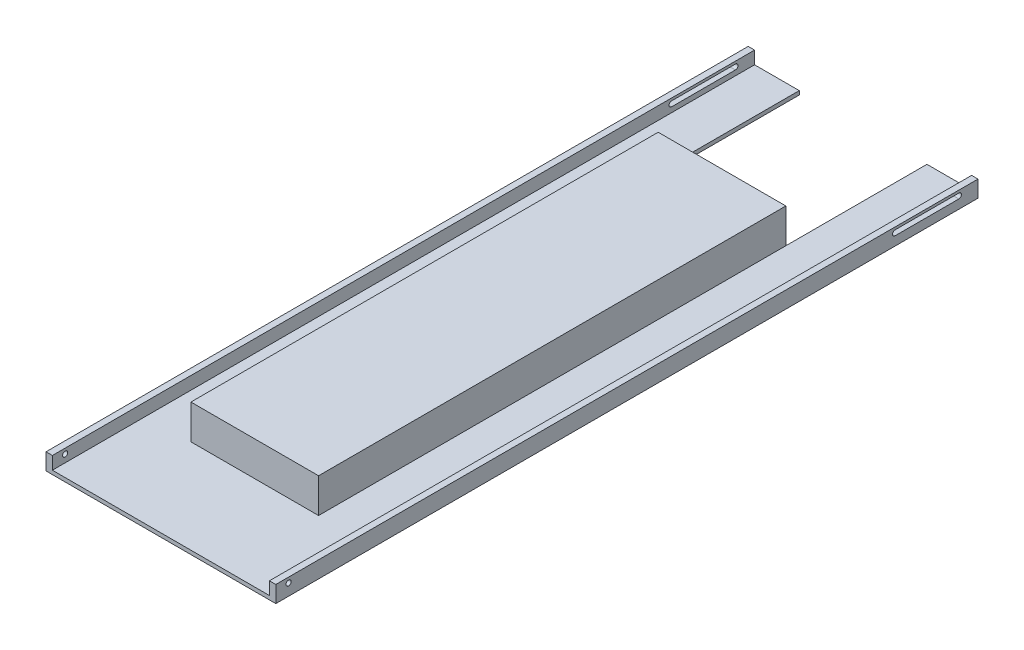
SolidWorks part; units mm, degrees
ref_plane "Front Plane" through (0, 0, 0) normal (0, 0, 1) x (1, 0, 0)
ref_plane "Top Plane" through (0, 0, 0) normal (0, 1, 0) x (1, 0, 0)
ref_plane "Right Plane" through (0, 0, 0) normal (1, 0, 0) x (0, 0, -1)
sketch "Sketch1" plane through (0, 0, 0) normal (0, 0, 1) x (1, 0, 0)
  line L0 (-165.6471, 7.8529) -> (-165.6471, -7.1471)
  line L1 (-165.6471, -7.1471) -> (14.3529, -7.1471)
  line L2 (14.3529, -7.1471) -> (14.3529, 7.8529)
  line L3 (14.3529, 7.8529) -> (9.3529, 7.8529)
  line L4 (9.3529, 7.8529) -> (9.3529, -2.1471)
  line L5 (9.3529, -2.1471) -> (-160.6471, -2.1471)
  line L6 (-160.6471, -2.1471) -> (-160.6471, 7.8529)
  line L7 (-160.6471, 7.8529) -> (-165.6471, 7.8529)
  dimension "D1" = 10
  dimension "D2" = 10
  dimension "D3" = 15
  dimension "D4" = 5
  dimension "D5" = 5
  dimension "D6" = 180
extrude "Boss-Extrude1" add sketch "Sketch1" along normal blind 550
sketch "Sketch2" plane through (14.3529, 0, 0) normal (1, 0, 0) x (0, 0, -1)
  line L0 (-550, -7.1471) -> (0, -7.1471) construction
  line L1 (-550, -7.1471) -> (-550, 7.8529) construction
  point P0 (-540, -0.1471)
  dimension "D1" = 7
  dimension "D2" = 10
hole_wizard "Ø4.0mm Dowel Hole1" positions "Sketch3" profile "Sketch4" hole size "Ø4.0" standard "ANSI Metric" end condition through all
sketch "Sketch3" plane through (14.3529, 0, 0) normal (1, 0, 0) x (0, 0, -1)
  point P0 (-540, -0.1471)
sketch "Sketch4" plane through (14.3529, -0.1471, 540) normal (0, 1, 0) x (0, 0, -1)
  line L0 (0, 0) -> (0, 180)
  line L1 (0, 180) -> (2, 180)
  line L2 (2, 180) -> (2, 0)
  line L5 (2, 0) -> (0, 0)
  line L11 (0, -6.35) -> (0, 107.95) construction
  dimension "Thru Hole Dia." = 4
  dimension "Thru Hole Depth" = 180
sketch "Sketch5" plane through (14.3529, 0, 0) normal (1, 0, 0) x (0, 0, -1)
  line L0 (0, -7.1471) -> (0, 7.8529) construction
  line L1 (-65, 1.8529) -> (-15, 1.8529)
  line L2 (-15, -2.1471) -> (-65, -2.1471)
  line L3 (-550, -7.1471) -> (0, -7.1471) construction
  arc A0 (-15, -2.1471) -> (-15, 1.8529) centre (-15, -0.1471) ccw
  arc A1 (-65, 1.8529) -> (-65, -2.1471) centre (-65, -0.1471) ccw
  point P4 (0, 0.3529)
  dimension "D2" = 4
  dimension "D3" = 4
  dimension "D1" = 15
  dimension "D4" = 50
  dimension "D5" = 5
extrude "Cut-Extrude1" cut sketch "Sketch5" against normal through all
sketch "Sketch7" plane through (0, -7.1471, 0) normal (0, -1, 0) x (1, 0, 0)
  line L0 (-165.6471, 0) -> (14.3529, 0) construction
  line L1 (-25.6471, 474.5) -> (-125.6471, 474.5)
  line L2 (-25.6471, 474.5) -> (-25.6471, 65)
  line L3 (-25.6471, 65) -> (-125.6471, 65)
  line L4 (-125.6471, 474.5) -> (-125.6471, 65)
  line L5 (-25.6471, 474.5) -> (-125.6471, 65) construction
  line L6 (-25.6471, 65) -> (-125.6471, 474.5) construction
  point P0 (-75.6471, 269.75)
  point P7 (-75.6471, 0)
  dimension "D1" = 65
  dimension "D2" = 409.5
  dimension "D3" = 100
extrude "Cut-Extrude2" cut sketch "Sketch7" against normal through all
sketch "Sketch8" plane through (0, -2.1471, 0) normal (0, 1, 0) x (1, 0, 0)
  line L0 (-125.6471, -474.5) -> (-25.6471, -474.5)
  line L1 (-125.6471, -474.5) -> (-125.6471, -476.5)
  line L2 (-25.6471, -474.5) -> (-25.6471, -476.5)
  line L3 (-125.6471, -476.5) -> (-25.6471, -476.5)
  dimension "D1" = 2
extrude "Boss-Extrude2" add sketch "Sketch8" along normal blind 23
sketch "Sketch9" plane through (0, 0, 474.5) normal (0, 0, -1) x (-1, 0, 0)
  line L0 (125.6471, 20.8529) -> (25.6471, 20.8529)
  line L1 (125.6471, 20.8529) -> (125.6471, 18.8529)
  line L2 (25.6471, 20.8529) -> (25.6471, 18.8529)
  line L3 (125.6471, 18.8529) -> (25.6471, 18.8529)
  dimension "D1" = 2
extrude "Boss-Extrude3" add sketch "Sketch9" along normal blind 364
sketch "Sketch10" plane through (0, -7.1471, 0) normal (0, -1, 0) x (1, 0, 0)
  line L0 (-125.6471, 65) -> (-25.6471, 65)
  line L1 (-125.6471, 65) -> (-125.6471, 0.0462)
  line L2 (-25.6471, 65) -> (-25.6471, 0.0462)
  line L3 (-125.6471, 0.0462) -> (-25.6471, 0.0462)
extrude "Cut-Extrude3" cut sketch "Sketch10" against normal blind 364
sketch "Sketch11" plane through (0, -7.1471, 0) normal (0, -1, 0) x (1, 0, 0)
  line L0 (-125.6471, 7.2807) -> (-25.6471, 7.2807)
  line L1 (-125.6471, 7.2807) -> (-125.6471, -28.4155)
  line L2 (-25.6471, 7.2807) -> (-25.6471, -28.4155)
  line L3 (-125.6471, -28.4155) -> (-25.6471, -28.4155)
  line L4 (-125.6471, 474.5) -> (-125.6471, 0.0462) construction
  line L5 (-25.6471, 0.0462) -> (-25.6471, 474.5) construction
extrude "Cut-Extrude4" cut sketch "Sketch11" against normal blind 364
sketch "Sketch12" plane through (0, 0, 0) normal (0, 0, -1) x (-1, 0, 0)
  line L0 (-9.3529, 7.8529) -> (-14.3529, 7.8529)
  line L1 (-9.3529, 7.8529) -> (-9.3529, 3.8529)
  line L2 (-14.3529, 7.8529) -> (-14.3529, 3.8529)
  line L3 (-9.3529, 3.8529) -> (-14.3529, 3.8529)
  line L4 (165.6471, 7.8529) -> (160.6471, 7.8529)
  line L5 (165.6471, 7.8529) -> (165.6471, 3.8529)
  line L6 (160.6471, 7.8529) -> (160.6471, 3.8529)
  line L7 (165.6471, 3.8529) -> (160.6471, 3.8529)
  dimension "D1" = 4
  dimension "D2" = 4
extrude "Cut-Extrude6" cut sketch "Sketch12" against normal through all
sketch "Sketch13" plane through (0, 0, 0) normal (0, 0, -1) x (-1, 0, 0)
  line L0 (25.6471, -2.1471) -> (-9.3529, -2.1471)
  line L2 (25.6471, -2.1471) -> (25.6471, -4.1471)
  line L3 (-9.3529, -2.1471) -> (-9.3529, -4.1471)
  line L4 (25.6471, -4.1471) -> (-9.3529, -4.1471)
  line L5 (160.6471, -2.1471) -> (125.6471, -2.1471)
  line L6 (160.6471, -2.1471) -> (160.6471, -4.1471)
  line L7 (125.6471, -2.1471) -> (125.6471, -4.1471)
  line L8 (160.6471, -4.1471) -> (125.6471, -4.1471)
  dimension "D1" = 2
  dimension "D2" = 2
extrude "Cut-Extrude7" cut sketch "Sketch13" against normal through all
sketch "Sketch14" plane through (0, -7.1471, 0) normal (0, -1, 0) x (1, 0, 0)
  line L8 (-165.6471, 0) -> (-125.6471, 0)
  line L9 (-125.6471, 0) -> (-125.6471, 474.5)
  line L10 (-125.6471, 474.5) -> (-25.6471, 474.5)
  line L11 (-25.6471, 474.5) -> (-25.6471, 0)
  line L12 (-25.6471, 0) -> (14.3529, 0)
  line L13 (14.3529, 0) -> (14.3529, 550)
  line L14 (14.3529, 550) -> (-165.6471, 550)
  line L15 (-165.6471, 550) -> (-165.6471, 0)
  line L16 (-165.6471, 0) -> (-125.6471, 0)
  line L17 (-125.6471, 0) -> (-125.6471, 474.5)
  line L18 (-125.6471, 474.5) -> (-25.6471, 474.5)
  line L19 (-25.6471, 474.5) -> (-25.6471, 0)
  line L20 (-25.6471, 0) -> (14.3529, 0)
  line L21 (14.3529, 0) -> (14.3529, 550)
  line L22 (14.3529, 550) -> (-165.6471, 550)
  line L23 (-165.6471, 550) -> (-165.6471, 0)
  dimension "D1" = 0
extrude "Boss-Extrude4" add sketch "Sketch14" along normal blind 2
sketch "Sketch15" plane through (0, 0, 0) normal (0, 0, -1) x (-1, 0, 0)
  line L0 (160.6471, -4.1471) -> (125.6471, -4.1471)
  line L1 (160.6471, -4.1471) -> (160.6471, -6.1471)
  line L2 (125.6471, -4.1471) -> (125.6471, -6.1471)
  line L3 (160.6471, -6.1471) -> (125.6471, -6.1471)
  line L4 (25.6471, -4.1471) -> (-9.3529, -4.1471)
  line L5 (25.6471, -4.1471) -> (25.6471, -6.1471)
  line L6 (-9.3529, -4.1471) -> (-9.3529, -6.1471)
  line L7 (25.6471, -6.1471) -> (-9.3529, -6.1471)
  dimension "D1" = 2
  dimension "D2" = 2
extrude "Cut-Extrude8" cut sketch "Sketch15" against normal through all
sketch "Sketch18" plane through (0, 0, 550) normal (0, 0, 1) x (1, 0, 0)
  line L0 (-25.6471, -6.1471) -> (-125.6471, -6.1471)
  line L1 (-25.6471, -6.1471) -> (-25.6471, 1.0028)
  line L2 (-125.6471, -6.1471) -> (-125.6471, 1.0028)
  line L3 (-25.6471, 1.0028) -> (-125.6471, 1.0028)
extrude "Cut-Extrude10" cut sketch "Sketch18" against normal up to surface (73.5 mm away) up to face at (-75.6471, 9.3529, 476.5)
sketch "Sketch22" plane through (0, 0, 474.5) normal (0, 0, -1) x (-1, 0, 0)
  line L0 (25.6471, 18.8529) -> (125.6471, 18.8529) construction
  line L1 (125.6471, -9.1471) -> (123.6471, -9.1471)
  line L2 (125.6471, -9.1471) -> (125.6471, 18.8529)
  line L3 (125.6471, 18.8529) -> (123.6471, 18.8529)
  line L4 (123.6471, -9.1471) -> (123.6471, 18.8529)
  dimension "D1" = 2
extrude "Boss-Extrude8" add sketch "Sketch22" along normal up to surface (364 mm away) up to face at (-75.6471, 19.8529, 110.5)
sketch "Sketch24" plane through (0, 0, 474.5) normal (0, 0, -1) x (-1, 0, 0)
  line L0 (25.6471, 18.8529) -> (123.6471, 18.8529) construction
  line L1 (25.6471, -9.1471) -> (27.6471, -9.1471)
  line L2 (25.6471, -9.1471) -> (25.6471, 18.8529)
  line L3 (25.6471, 18.8529) -> (27.6471, 18.8529)
  line L4 (27.6471, -9.1471) -> (27.6471, 18.8529)
  dimension "D1" = 2
extrude "Boss-Extrude9" add sketch "Sketch24" along normal up to surface (364 mm away) up to face at (-96.5042, 7.8529, 110.5)
